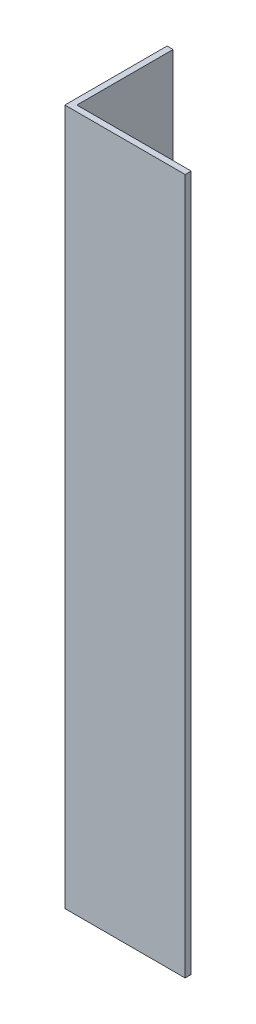
SolidWorks part; units mm, degrees
material "Acrylic (Medium-high impact)"
ref_plane "Front Plane" through (0, 0, 0) normal (0, 0, 1) x (1, 0, 0)
ref_plane "Top Plane" through (0, 0, 0) normal (0, 1, 0) x (1, 0, 0)
ref_plane "Right Plane" through (0, 0, 0) normal (1, 0, 0) x (0, 0, -1)
sketch "Sketch1" plane through (0, 0, 0) normal (0, 0, 1) x (1, 0, 0)
  line L0 (-406.4, 457.2) -> (-406.4, -457.2) construction
  line L1 (-406.4, 457.2) -> (-400.05, 457.2)
  line L2 (-406.4, 457.2) -> (-406.4, -277.5418)
  line L3 (-406.4, -277.5418) -> (-400.05, -277.5418)
  line L4 (-400.05, 457.2) -> (-400.05, -277.5418)
  line L5 (812.8, -277.5418) -> (-406.4, -277.5418) construction
  line L6 (812.8, -277.5418) -> (-406.4, -277.5418) construction
  line L7 (812.8, 457.2) -> (-406.4, 457.2) construction
  line L8 (812.8, 457.2) -> (-406.4, 457.2) construction
  dimension "D1" = 6.35
extrude "Boss-Extrude1" add sketch "Sketch1" along normal blind 107.95
sketch "Sketch2" plane through (-400.05, 0, 0) normal (1, 0, 0) x (0, 0, -1)
  line L0 (-107.95, -277.5418) -> (0, -277.5418) construction
  line L1 (-107.95, 457.2) -> (-101.6, 457.2)
  line L2 (-107.95, 457.2) -> (-107.95, -277.5418)
  line L3 (-107.95, -277.5418) -> (-101.6, -277.5418)
  line L4 (-101.6, 457.2) -> (-101.6, -277.5418)
  dimension "D1" = 6.35
extrude "Boss-Extrude2" add sketch "Sketch2" along normal blind 120.65
